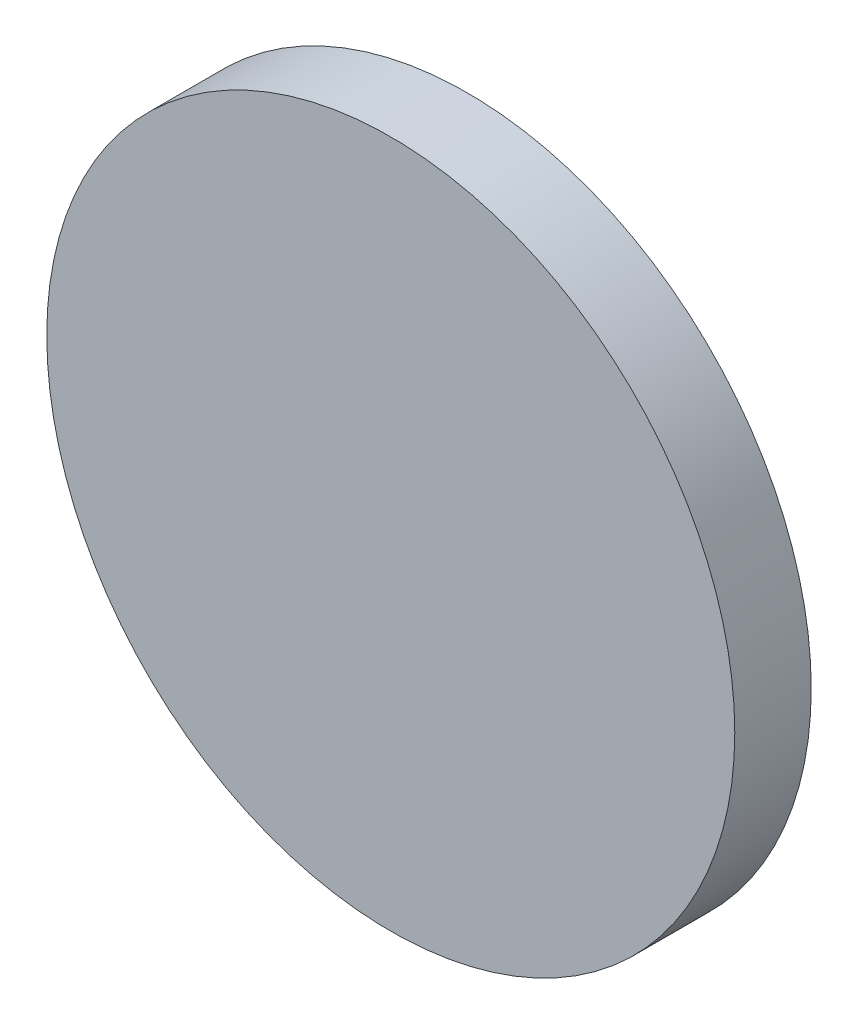
SolidWorks part; units mm, degrees
ref_plane "Front Plane" through (0, 0, 0) normal (0, 0, 1) x (1, 0, 0)
ref_plane "Top Plane" through (0, 0, 0) normal (0, 1, 0) x (1, 0, 0)
ref_plane "Right Plane" through (0, 0, 0) normal (1, 0, 0) x (0, 0, -1)
sketch "Sketch1" plane through (0, 0, 0) normal (0, 0, 1) x (1, 0, 0)
  line L0 (0, 0) -> (0, 19) construction
  circle A0 centre (0, 0) radius 22.5
  circle A1 centre (0, 0) radius 19 construction
  point P19 (0, 0)
  dimension "D1" = 38
  dimension "D2" = 45
extrude "Boss-Extrude1" add sketch "Sketch1" along normal blind 5
